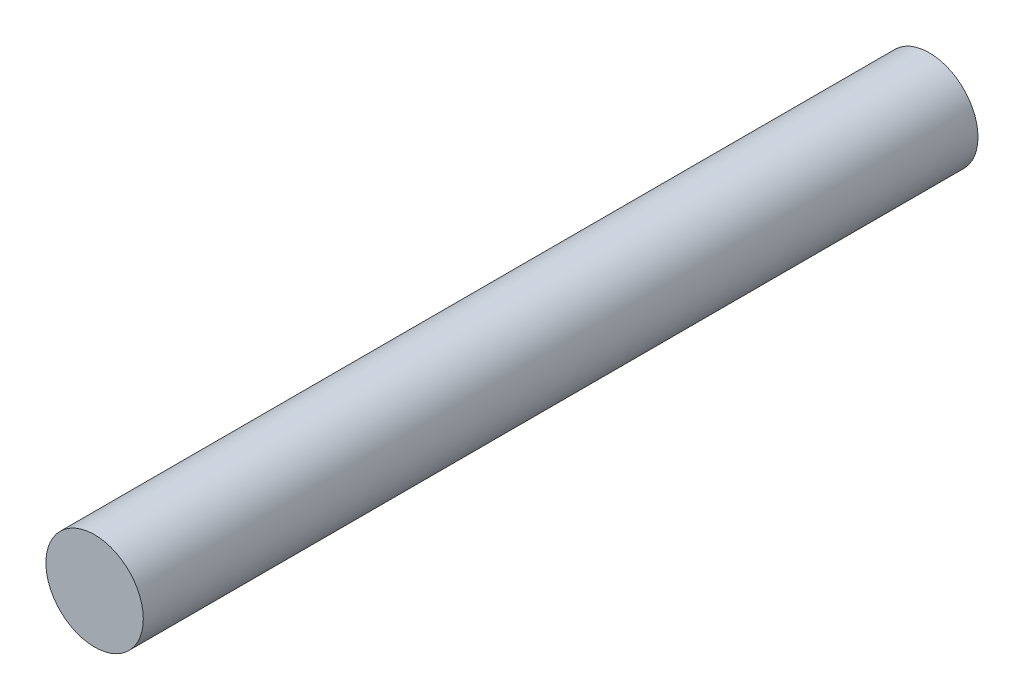
SolidWorks part; units mm, degrees
ref_plane "前视基准面" through (0, 0, 0) normal (0, 0, 1) x (1, 0, 0)
ref_plane "上视基准面" through (0, 0, 0) normal (0, 1, 0) x (1, 0, 0)
ref_plane "右视基准面" through (0, 0, 0) normal (1, 0, 0) x (0, 0, -1)
other "Configuration Table"
sketch "草图1" plane through (0, 0, 0) normal (0, 0, 1) x (1, 0, 0)
  circle A0 centre (0, 0) radius 17.5
extrude "凸台-拉伸1" add sketch "草图1" along normal blind 300
